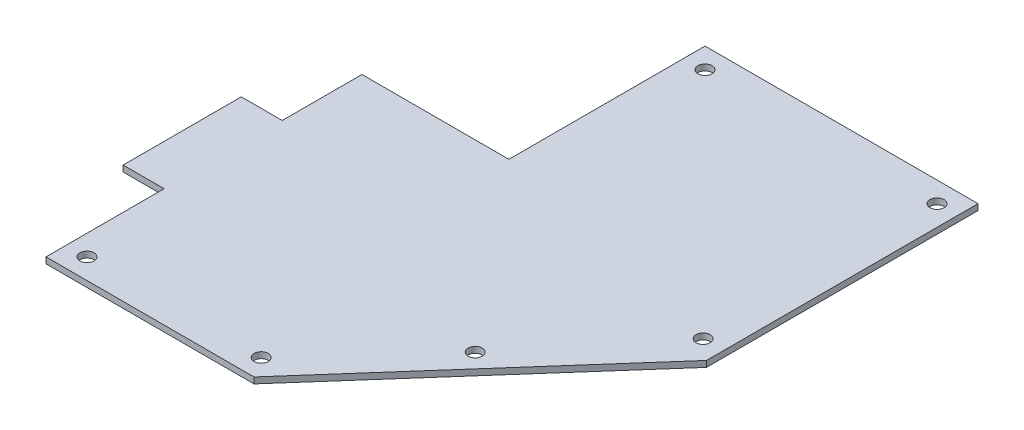
SolidWorks part; units mm, degrees
ref_plane "Front Plane" through (0, 0, 0) normal (0, 0, 1) x (1, 0, 0)
ref_plane "Top Plane" through (0, 0, 0) normal (0, 1, 0) x (1, 0, 0)
ref_plane "Right Plane" through (0, 0, 0) normal (1, 0, 0) x (0, 0, -1)
sketch "Sketch1" plane through (0, 0, 0) normal (0, 1, 0) x (1, 0, 0)
  line L0 (0, 0) -> (-67.7, 0)
  line L1 (-67.7, 0) -> (-67.7, -48.64)
  line L2 (-67.7, -48.64) -> (-104.14, -48.64)
  line L3 (-104.14, -48.64) -> (-104.14, -68.4097)
  line L4 (-104.14, -68.4097) -> (-114.3, -68.4097)
  line L5 (0, 0) -> (0, -67.34)
  line L6 (0, -67.34) -> (-52.5601, -126.9997)
  line L7 (-52.5601, -126.9997) -> (-104.1401, -126.9997)
  line L8 (-104.1401, -126.9997) -> (-104.1401, -97.7097)
  line L9 (-104.1401, -97.7097) -> (-114.3001, -97.7097)
  line L10 (-114.3, -68.4097) -> (-114.3001, -97.7097)
  dimension "D1" = 67.7
  dimension "D2" = 48.64
  dimension "D3" = 36.44
  dimension "D4" = 29.3
  dimension "D5" = 10.16
  dimension "D6" = 67.34
  dimension "D7" = 79.51
  dimension "D8" = 138.62
  dimension "D9" = 51.58
  dimension "D10" = 29.29
  dimension "D11" = 10.16
extrude "Boss-Extrude1" add sketch "Sketch1" along normal blind 1.5
sketch "Sketch2" plane through (0, 1.5, 0) normal (0, 1, 0) x (1, 0, 0)
  line L0 (0, 0) -> (-67.7, 0) construction
  line L1 (0, -67.34) -> (0, 0) construction
  line L2 (-67.7, 0) -> (-67.7, -48.64) construction
  line L3 (-52.5601, -126.9997) -> (0, -67.34) construction
  line L4 (-104.1401, -97.7097) -> (-104.1401, -126.9997) construction
  line L5 (-104.1401, -126.9997) -> (-52.5601, -126.9997) construction
  point P0 (-5.08, -5.08)
  point P1 (-62.62, -5.08)
  point P8 (-5.08, -63.08)
  point P9 (-30.4665, -94.237)
  point P14 (-99.0601, -121.9197)
  point P17 (-55.8501, -121.9197)
  dimension "D1" = 5.08
  dimension "D2" = 5.08
  dimension "D3" = 5.08
  dimension "D4" = 5.08
  dimension "D5" = 58
  dimension "D6" = 5.08
  dimension "D7" = 5.08
  dimension "D8" = 40.19
  dimension "D9" = 5.08
  dimension "D10" = 5.08
  dimension "D11" = 43.21
  dimension "D12" = 5.08
hole_wizard "Ø4.0mm Dowel Hole1" positions "3DSketch1" profile "Sketch3" hole size "Ø4.0" standard "ANSI Metric"
sketch3d "3DSketch1"
  point P3 (-99.0601, 1.5, 121.9197)
  point P6 (-55.8501, 1.5, 121.9197)
  point P9 (-5.08, 1.5, 63.08)
  point P12 (-30.4665, 1.5, 94.237)
  point P15 (-5.08, 1.5, 5.08)
  point P18 (-62.62, 1.5, 5.08)
sketch "Sketch3" plane through (-99.0601, 1.5, 121.9197) normal (1, 0, 0) x (0, 0, 1)
  line L0 (0, 0) -> (0, 1.5)
  line L1 (0, 1.5) -> (1.75, 1.5)
  line L2 (1.75, 1.5) -> (1.75, 0)
  line L5 (1.75, 0) -> (0, 0)
  line L10 (0, 1.5) -> (-1.75, 1.5) construction
  line L11 (0, -6.35) -> (0, 107.95) construction
  dimension "Hole Dia." = 3.5
  dimension "Hole Depth" = 1.5
  dimension "Drill Angle" = 180
